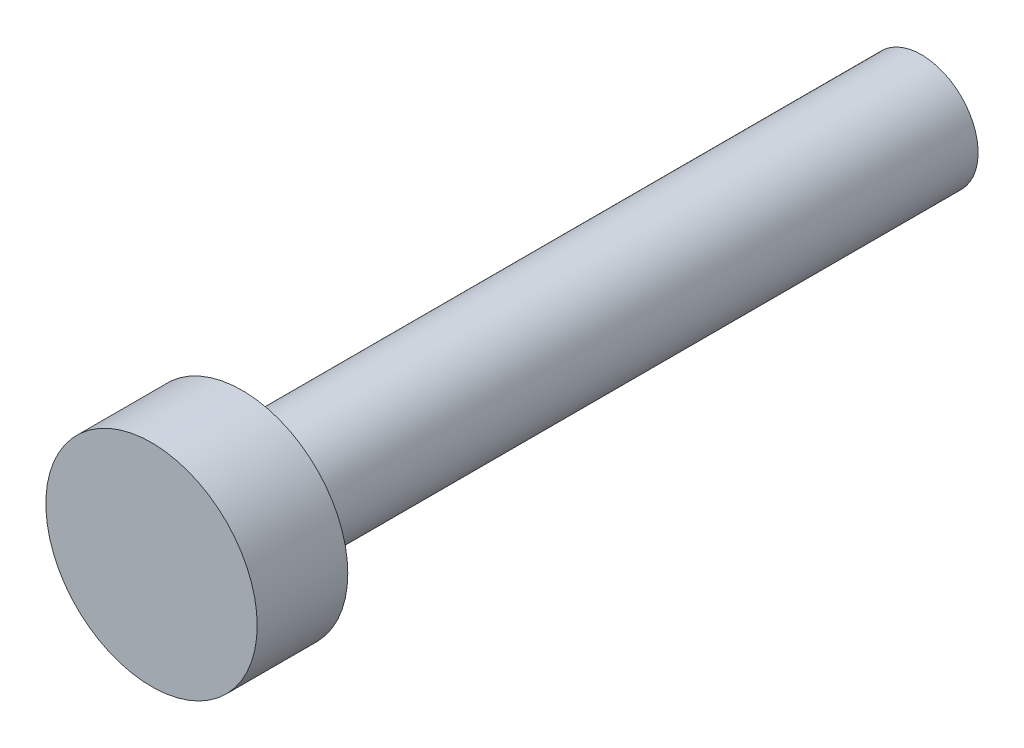
SolidWorks part; units mm, degrees
ref_plane "Plan de face" through (0, 0, 0) normal (0, 0, 1) x (1, 0, 0)
ref_plane "Plan de dessus" through (0, 0, 0) normal (0, 1, 0) x (1, 0, 0)
ref_plane "Plan de droite" through (0, 0, 0) normal (1, 0, 0) x (0, 0, -1)
sketch "Esquisse1" plane through (0, 0, 0) normal (0, 0, 1) x (1, 0, 0)
  circle A0 centre (0, 0) radius 2.8
  dimension "D1" = 5.6
extrude "Boss.-Extru.1" add sketch "Esquisse1" along normal blind 2.4
sketch "Esquisse2" plane through (0, 0, 0) normal (0, 0, -1) x (-1, 0, 0)
  circle A0 centre (0, 0) radius 1.5
  dimension "D1" = 3
extrude "Boss.-Extru.2" add sketch "Esquisse2" along normal blind 18
